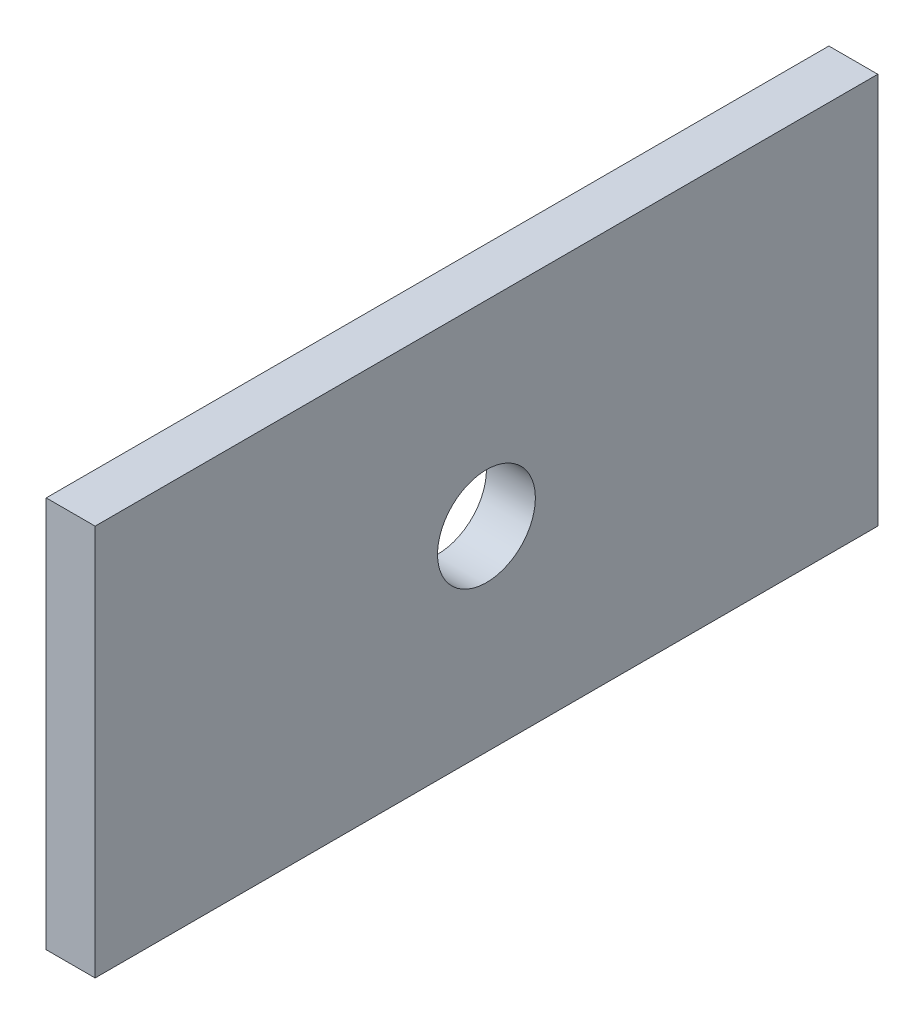
SolidWorks part; units mm, degrees
ref_plane "Front Plane" through (0, 0, 0) normal (0, 0, 1) x (1, 0, 0)
ref_plane "Top Plane" through (0, 0, 0) normal (0, 1, 0) x (1, 0, 0)
ref_plane "Right Plane" through (0, 0, 0) normal (1, 0, 0) x (0, 0, -1)
sketch "Sketch1" plane through (0, 0, 0) normal (1, 0, 0) x (0, 0, -1)
  line L1 (-25.4, 12.7) -> (25.4, 12.7)
  line L2 (-25.4, 12.7) -> (-25.4, -12.7)
  line L3 (-25.4, -12.7) -> (25.4, -12.7)
  line L4 (25.4, 12.7) -> (25.4, -12.7)
  line L5 (-25.4, 12.7) -> (25.4, -12.7) construction
  line L6 (-25.4, -12.7) -> (25.4, 12.7) construction
  point P0 (0, 0)
extrude "Boss-Extrude1" add sketch "Sketch1" along normal blind 3.175
sketch "Sketch2" plane through (3.175, 0, 0) normal (1, 0, 0) x (0, 0, -1)
  circle A0 centre (0, 0) radius 3.175
extrude "Cut-Extrude1" cut sketch "Sketch2" against normal through all
